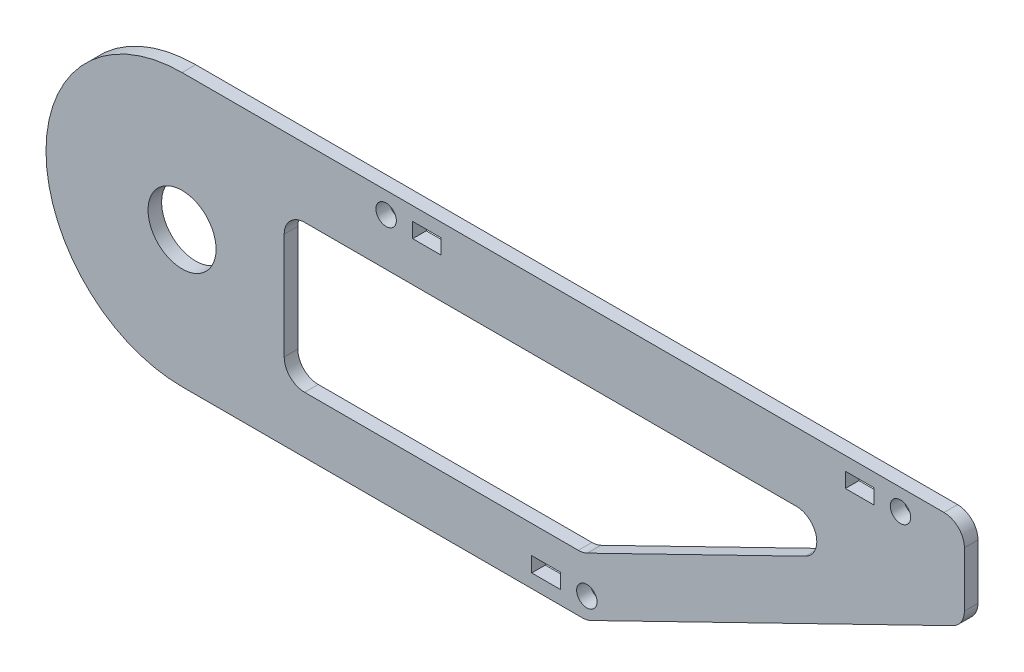
SolidWorks part; units mm, degrees
ref_plane "前视基准面" through (0, 0, 0) normal (0, 0, 1) x (1, 0, 0)
ref_plane "上视基准面" through (0, 0, 0) normal (0, 1, 0) x (1, 0, 0)
ref_plane "右视基准面" through (0, 0, 0) normal (1, 0, 0) x (0, 0, -1)
sketch "草图1" plane through (0, 0, 0) normal (0, 0, 1) x (1, 0, 0)
  line L0 (0, 20) -> (112, 20)
  line L1 (115, 20) -> (115, -20) construction
  line L2 (115, -20) -> (0, -20) construction
  line L4 (59.5675, -11.3939) -> (91.6185, 4.2351)
  line L11 (90.3036, 9.9316) -> (18.0131, 9.9316)
  line L12 (15.0131, 6.9316) -> (15.0131, -8.6974)
  line L15 (18.0131, -11.6974) -> (58.2527, -11.6974)
  line L21 (60.1224, -19.6965) -> (113.3149, 6.2417)
  line L22 (0, -20) -> (58.8075, -20)
  line L23 (115, 8.9382) -> (115, 17)
  line L35 (101.7, 15.8) -> (97.5, 15.8)
  line L36 (105, 12) -> (117, 12) construction
  line L39 (101.7, 15.8) -> (101.7, 18)
  line L40 (33.9, 18) -> (38.1, 18)
  line L41 (33.9, 18) -> (33.9, 15.8)
  line L42 (33.9, 15.8) -> (38.1, 15.8)
  line L43 (38.1, 18) -> (38.1, 15.8)
  line L48 (30, 16.9) -> (33.9, 16.9) construction
  line L49 (101.7, 18) -> (97.5, 18)
  line L50 (97.5, 15.8) -> (97.5, 18)
  line L51 (105.6, 16.9) -> (101.7, 16.9) construction
  line L52 (105.6, 16.9) -> (101.7, 16.9) construction
  line L57 (59.5, -16.9) -> (55.6, -16.9) construction
  line L58 (59.5, -16.9) -> (55.6, -16.9) construction
  line L59 (51.4, -15.8) -> (51.4, -18)
  line L65 (55.6, -18) -> (51.4, -18)
  line L66 (55.6, -15.8) -> (55.6, -18)
  line L67 (55.6, -15.8) -> (51.4, -15.8)
  line L68 (59.5, -20) -> (59.5, -16.9) construction
  circle A0 centre (0, 0) radius 5
  circle A1 centre (0, 0) radius 20 construction
  arc A2 (0, -20) -> (0, 20) centre (0, 0) cw
  arc A5 (59.5675, -11.3939) -> (58.2527, -11.6974) centre (58.2527, -8.6974) cw
  circle A13 centre (30, 16.9) radius 1.5
  circle A14 centre (105.6, 16.9) radius 1.5
  circle A17 centre (59.5, -16.9) radius 1.5
  arc A18 (15.0131, -8.6974) -> (18.0131, -11.6974) centre (18.0131, -8.6974) ccw
  arc A19 (15.0131, 6.9316) -> (18.0131, 9.9316) centre (18.0131, 6.9316) cw
  arc A20 (91.6185, 4.2351) -> (90.3036, 9.9316) centre (90.3036, 6.9316) ccw
  arc A21 (58.8075, -20) -> (60.1224, -19.6965) centre (58.8075, -17) ccw
  arc A22 (115, 17) -> (112, 20) centre (112, 17) ccw
  arc A23 (115, 8.9382) -> (113.3149, 6.2417) centre (112, 8.9382) cw
  point P11 (112.497, 12.562)
  point P13 (110.429, 10.8344)
  point P14 (108.5774, 9.9316)
  point P15 (110.429, 11.1196)
  point P16 (59.5, -14.0063)
  point P17 (58.9451, -11.6974)
  point P37 (115, 7.0634)
  point P58 (33.9, 16.9)
  dimension "D1" = 10
  dimension "D2" = 3
  dimension "D8" = 3
  dimension "D13" = 3
  dimension "D4" = 3
  dimension "D3" = 115
  dimension "D9" = 4.2
  dimension "D10" = 2.2
  dimension "D11" = 3.9
  dimension "D12" = 2
  dimension "D14" = 4.2
  dimension "D15" = 2.2
  dimension "D16" = 3.9
  dimension "D17" = 59.4
  dimension "D18" = 30
  dimension "D5" = 13.3
  dimension "D6" = 31.6
extrude "凸台-拉伸1" add sketch "草图1" along normal blind 2
